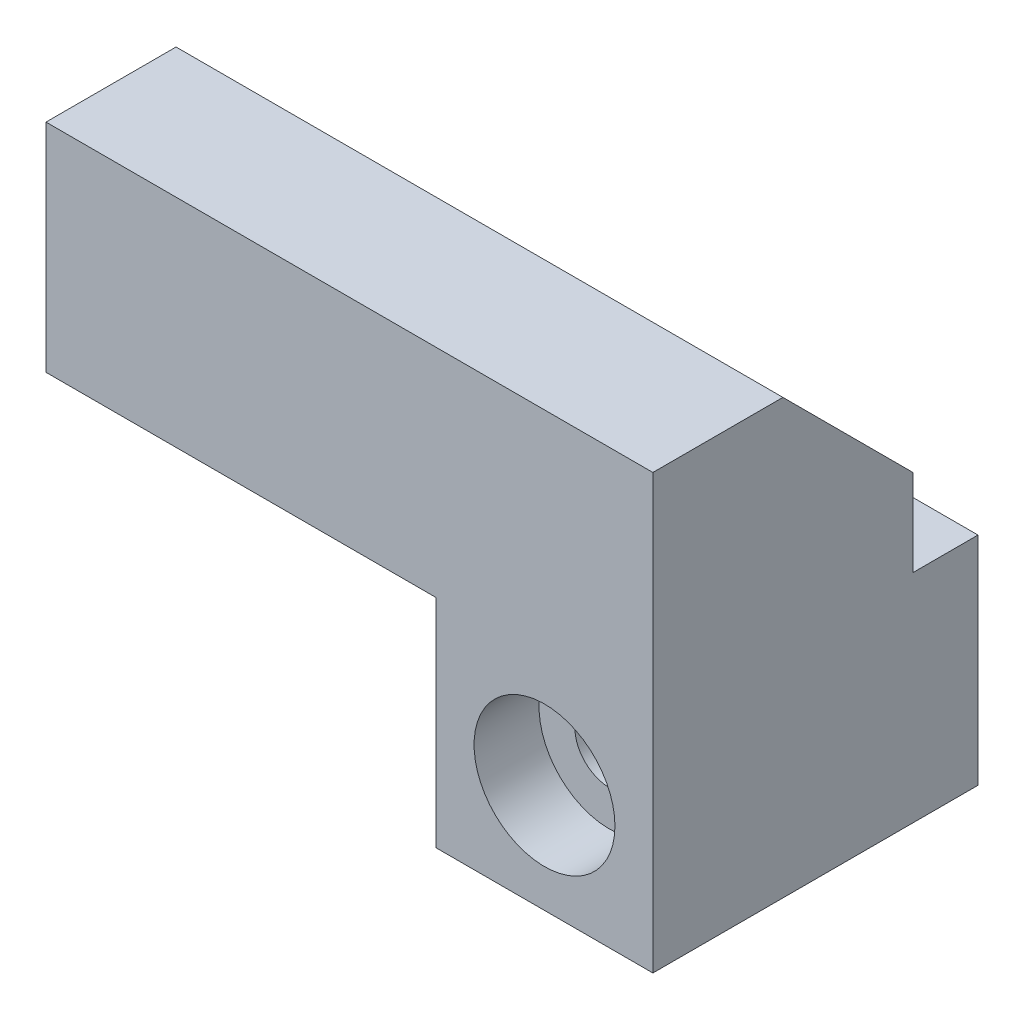
SolidWorks part; units mm, degrees
ref_plane "Front Plane" through (0, 0, 0) normal (0, 0, 1) x (1, 0, 0)
ref_plane "Top Plane" through (0, 0, 0) normal (0, 1, 0) x (1, 0, 0)
ref_plane "Right Plane" through (0, 0, 0) normal (1, 0, 0) x (0, 0, -1)
sketch "Sketch1" plane through (0, 0, 0) normal (0, 1, 0) x (1, 0, 0)
  line L1 (0, 0) -> (-28, 0)
  line L2 (0, 0) -> (0, 12)
  line L3 (0, 12) -> (-10, 12)
  line L4 (-28, 0) -> (-28, 6)
  line L7 (-28, 6) -> (-10, 6)
  line L8 (-10, 12) -> (-10, 6)
  dimension "D1" = 12
  dimension "D2" = 6
  dimension "D3" = 18
  dimension "D4" = 10
extrude "Boss-Extrude1" add sketch "Sketch1" along normal mid plane 10
sketch "Sketch4" plane through (0, -5, 0) normal (0, -1, 0) x (1, 0, 0)
  line L1 (-10, -12) -> (0, -12)
  line L2 (-10, -12) -> (-10, 0)
  line L3 (-10, 0) -> (0, 0)
  line L4 (0, -12) -> (0, 0)
extrude "Boss-Extrude2" add sketch "Sketch4" along normal blind 10
hole_wizard "CBORE for M3 Hex Socket Head Cap Screw1" positions "Sketch3" profile "Sketch2" counterbore size "M3" standard "DIN" end condition through all
sketch "Sketch3" plane through (0, 0, 0) normal (0, 0, 1) x (1, 0, 0)
  line L2 (-5, -10) -> (-5, -15) construction
  line L4 (0, -15) -> (-10, -15) construction
  line L5 (-5, -10) -> (0, -10) construction
  line L6 (0, 5) -> (0, -15) construction
  point P0 (-5, -10)
sketch "Sketch2" plane through (-5, -10, 0) normal (1, 0, 0) x (0, -1, 0)
  line L0 (0, 0) -> (0, 12)
  line L1 (0, 12) -> (1.6, 12)
  line L3 (1.6, 12) -> (1.6, 3)
  line L4 (1.6, 3) -> (3.25, 3)
  line L5 (3.25, 3) -> (3.25, 0)
  line L7 (3.25, 0) -> (0, 0)
  line L11 (0, -6.35) -> (0, 107.95) construction
  dimension "Thru Hole Dia." = 3.2
  dimension "Thru Hole Depth" = 12
  dimension "C'Bore Dia." = 6.5
  dimension "C'Bore Depth" = 3
chamfer "Chamfer1" distance 6 angle 45 1 edges at (-5, 5, -12)
sketch "Sketch5" plane through (0, 0, -12) normal (0, 0, -1) x (-1, 0, 0)
  line L0 (10, -1) -> (10, -15) construction
  line L1 (0, -15) -> (10, -15)
  line L2 (0, -15) -> (0, -5)
  line L3 (0, -5) -> (10, -5)
  line L4 (10, -15) -> (10, -5)
  line L5 (5, -10) -> (10, -10) construction
  circle A0 centre (5, -10) radius 1.6
  circle A1 centre (5, -10) radius 1.6 construction
extrude "Boss-Extrude3" add sketch "Sketch5" along normal blind 3
sketch "Sketch6" plane through (0, 0, -15) normal (0, 0, -1) x (-1, 0, 0)
  line L1 (5, -13.2332) -> (7.8, -11.6166)
  line L2 (7.8, -11.6166) -> (7.8, -8.3834)
  line L3 (7.8, -8.3834) -> (5, -6.7668)
  line L4 (5, -6.7668) -> (2.2, -8.3834)
  line L5 (2.2, -8.3834) -> (2.2, -11.6166)
  line L6 (2.2, -11.6166) -> (5, -13.2332)
  circle A0 centre (5, -10) radius 2.8 construction
  dimension "D1" = 5.6
extrude "Cut-Extrude1" cut sketch "Sketch6" against normal blind 4
